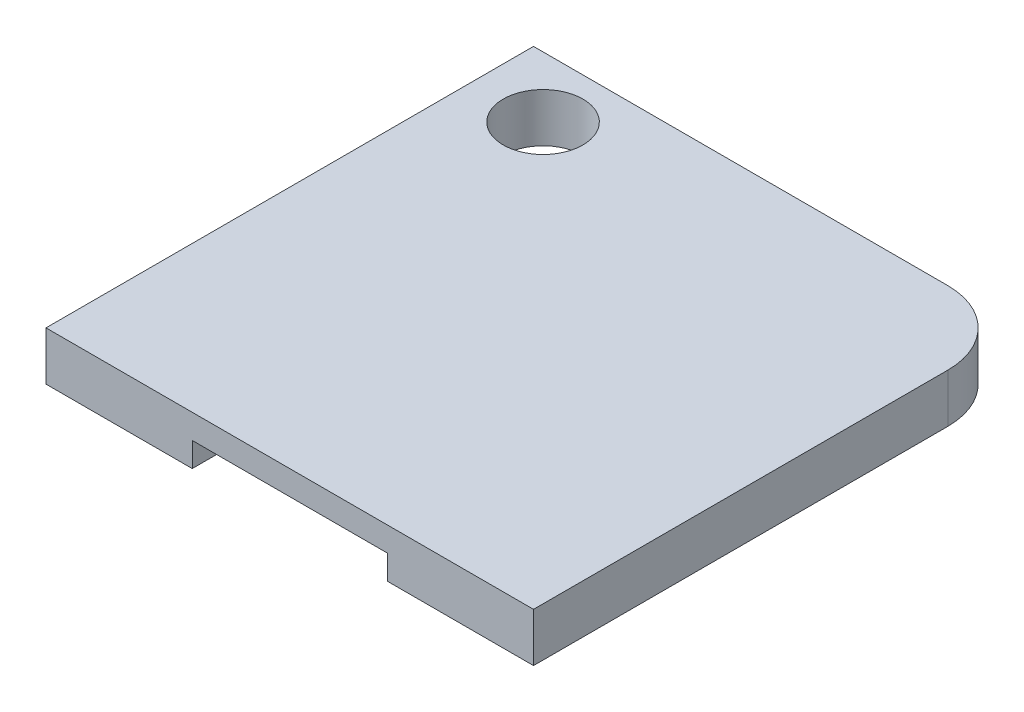
SolidWorks part; units mm, degrees
ref_plane "Front Plane" through (0, 0, 0) normal (0, 0, 1) x (1, 0, 0)
ref_plane "Top Plane" through (0, 0, 0) normal (0, 1, 0) x (1, 0, 0)
ref_plane "Right Plane" through (0, 0, 0) normal (1, 0, 0) x (0, 0, -1)
sketch "Sketch1" plane through (0, 0, 0) normal (0, 1, 0) x (1, 0, 0)
  line L1 (0, 0) -> (200, 0)
  line L2 (0, 0) -> (0, 200)
  line L3 (0, 200) -> (170, 200)
  line L4 (200, 0) -> (200, 170)
  line L5 (60, 0) -> (140, 0)
  line L6 (60, 0) -> (60, 50)
  line L7 (60, 50) -> (140, 50)
  line L8 (140, 0) -> (140, 50)
  line L9 (155.774, 138.0835) -> (186.2408, 138.0835)
  line L10 (155.774, 138.0835) -> (155.774, 108.5995)
  line L11 (155.774, 108.5995) -> (186.2408, 108.5995)
  line L12 (186.2408, 138.0835) -> (186.2408, 108.5995)
  circle A0 centre (25, 175) radius 12.5
  arc A2 (200, 170) -> (170, 200) centre (170, 170) ccw
  point P13 (200, 200)
  dimension "D3" = 25
  dimension "D9" = 30
  dimension "D1" = 200
  dimension "D2" = 200
  dimension "D4" = 25
  dimension "D5" = 25
  dimension "D6" = 50
  dimension "D7" = 80
  dimension "D8" = 60
extrude "Boss-Extrude1" add sketch "Sketch1" along normal blind 20 contours L2 L3 A2 L4 L1
sketch "Sketch5" plane through (0, 0, 0) normal (0, -1, 0) x (1, 0, 0)
  circle A0 centre (28.8266, -175.0887) radius 16.3356
extrude "Cut-Extrude1" cut sketch "Sketch5" against normal blind 20 contours A0
sketch "Sketch6" plane through (0, 0, 0) normal (0, -1, 0) x (-1, 0, 0)
  line L0 (0, 0) -> (-200, 0) construction
  line L1 (-60, 0) -> (-140, 0)
  line L2 (-60, 0) -> (-60, 15)
  line L3 (-65, 20) -> (-140, 20)
  line L4 (-140, 0) -> (-140, 20)
  line L5 (-200, 0) -> (-200, 170) construction
  arc A0 (-60, 15) -> (-65, 20) centre (-65, 15) ccw
  point P11 (-60, 20)
  dimension "D4" = 5
  dimension "D1" = 80
  dimension "D2" = 60
  dimension "D3" = 20
extrude "Cut-Extrude2" cut sketch "Sketch6" against normal blind 10
sketch "Sketch7" plane through (0, 0, 0) normal (0, -1, 0) x (1, 0, 0)
  line L0 (0, 0) -> (0, -200) construction
  line L1 (0, -100) -> (200, -100) construction
  line L2 (200, 0) -> (200, -170) construction
  line L4 (55, -103) -> (145, -103)
  line L5 (55, -103) -> (55, -106)
  line L6 (55, -106) -> (145, -106)
  line L7 (145, -103) -> (145, -106)
  text T0 "<i>ULB FABLAB</i>" font "Century Gothic" height 8
  point P9 (100, -103)
  point P12 (100, -100)
  dimension "D1" = 60
  dimension "D2" = 3
  dimension "D3" = 3
  dimension "D4" = 90
extrude "Cut-Extrude3" cut sketch "Sketch7" against normal blind 3
sketch "Sketch9" plane through (0, 0, 0) normal (0, -1, 0) x (-1, 0, 0)
  line L0 (-145, 106) -> (-145, 103) construction
  line L1 (-45, 120) -> (-155, 120)
  line L2 (-45, 120) -> (-45, 155)
  line L3 (-45, 155) -> (-155, 155)
  line L4 (-155, 120) -> (-155, 155)
  line L5 (0, 200) -> (-170, 200) construction
  dimension "D1" = 110
  dimension "D2" = 35
  dimension "D3" = 10
  dimension "D4" = 45
extrude "Cut-Extrude4" cut sketch "Sketch9" against normal blind 8
sketch "Sketch10" plane through (0, 0, 0) normal (0, -1, 0) x (1, 0, 0)
  line L1 (-2.4954, 2.2157) -> (203.614, 2.2157)
  line L2 (-2.4954, 2.2157) -> (-2.4954, -204.7326)
  line L3 (-2.4954, -204.7326) -> (203.614, -204.7326)
  line L4 (203.614, 2.2157) -> (203.614, -204.7326)
